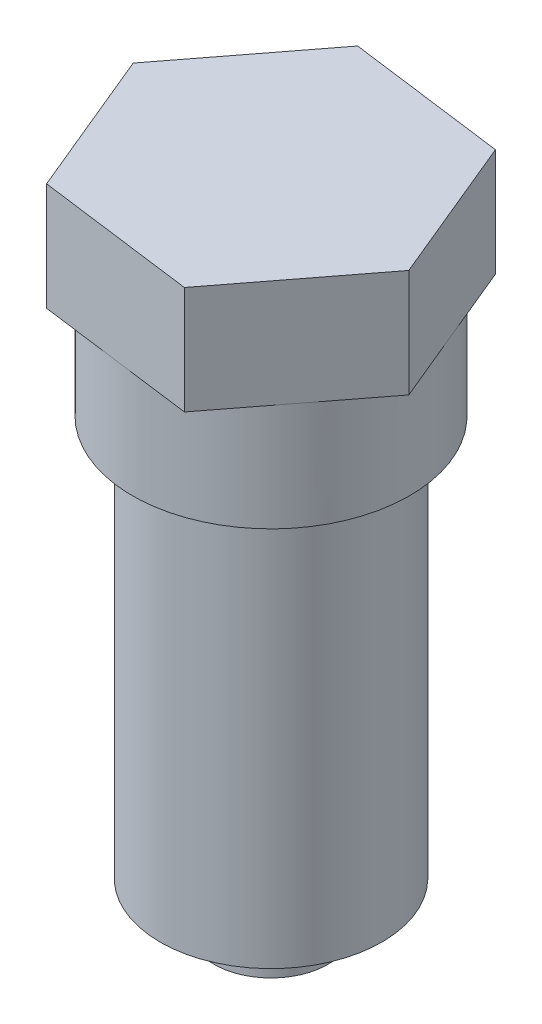
SolidWorks part; units mm, degrees
ref_plane "前视基准面" through (0, 0, 0) normal (0, 0, 1) x (1, 0, 0)
ref_plane "上视基准面" through (0, 0, 0) normal (0, 1, 0) x (1, 0, 0)
ref_plane "右视基准面" through (0, 0, 0) normal (1, 0, 0) x (0, 0, -1)
other "Configuration Table"
sketch "草图1" plane through (0, 0, 0) normal (0, 1, 0) x (1, 0, 0)
  line L1 (6.3259, 8.2452) -> (-3.9776, 9.601)
  line L2 (-3.9776, 9.601) -> (-10.3035, 1.3558)
  line L3 (-10.3035, 1.3558) -> (-6.3259, -8.2452)
  line L4 (-6.3259, -8.2452) -> (3.9776, -9.601)
  line L5 (3.9776, -9.601) -> (10.3035, -1.3558)
  line L6 (10.3035, -1.3558) -> (6.3259, 8.2452)
  circle A0 centre (0, 0) radius 9 construction
  dimension "D1" = 18
extrude "凸台-拉伸1" add sketch "草图1" along normal blind 7
sketch "草图2" plane through (0, 0, 0) normal (0, -1, 0) x (1, 0, 0)
  circle A0 centre (0, 0) radius 9
extrude "凸台-拉伸2" add sketch "草图2" along normal blind 7
sketch "草图3" plane through (0, -7, 0) normal (0, -1, 0) x (1, 0, 0)
  circle A0 centre (0, 0) radius 7.2
  dimension "D1" = 14.4
extrude "凸台-拉伸3" add sketch "草图3" along normal blind 26
sketch "草图4" plane through (0, -33, 0) normal (0, -1, 0) x (1, 0, 0)
  circle A0 centre (0, 0) radius 3.7
  dimension "D1" = 7.4
extrude "凸台-拉伸4" add sketch "草图4" along normal blind 3
